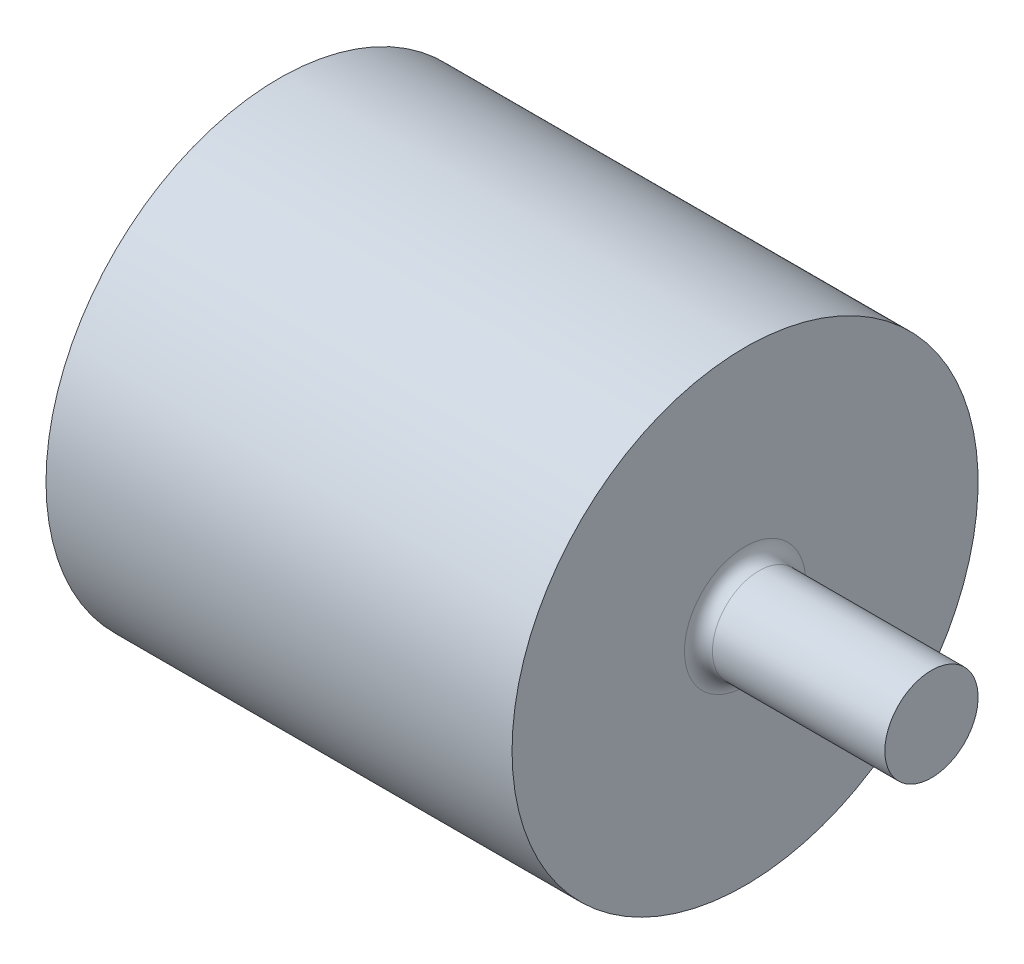
SolidWorks part; units mm, degrees
material "1.4305 (X8CrNiS18-9)"
ref_plane "Vorne" through (0, 0, 0) normal (0, 0, 1) x (1, 0, 0)
ref_plane "Oben" through (0, 0, 0) normal (0, 1, 0) x (1, 0, 0)
ref_plane "Rechts" through (0, 0, 0) normal (1, 0, 0) x (0, 0, -1)
sketch "Skizze1" plane through (0, 0, 0) normal (0, 0, 1) x (1, 0, 0)
  line L0 (0, -55) -> (0, 55) construction
  line L1 (-4.9935, 5) -> (5.0065, 5)
  line L2 (-4.9935, 5) -> (-4.9935, 0)
  line L3 (-4.9935, 0) -> (4.9804, 0)
  line L4 (5.0065, 5) -> (5.0065, 1)
  line L5 (-4.9935, 5) -> (4.9804, 0) construction
  line L6 (-4.9935, 0) -> (5.0065, 5) construction
  line L7 (55, 0) -> (-55, 0) construction
  line L8 (-0.0065, 0) -> (21.8681, 0) construction
  line L10 (4.9804, 0) -> (9.0065, 0)
  line L12 (5.0065, 1) -> (9.0065, 1)
  line L13 (9.0065, 0) -> (9.0065, 1)
  point P0 (0, 2.4967)
  dimension "D1" = 10
  dimension "D2" = 10
  dimension "D3" = 2
  dimension "D4" = 4
revolve "Rotation1" add sketch "Skizze1" angle 360 about L8
fillet "Verrundung1" radius 0.3 1 edges at (5.0065, 0, 1)
